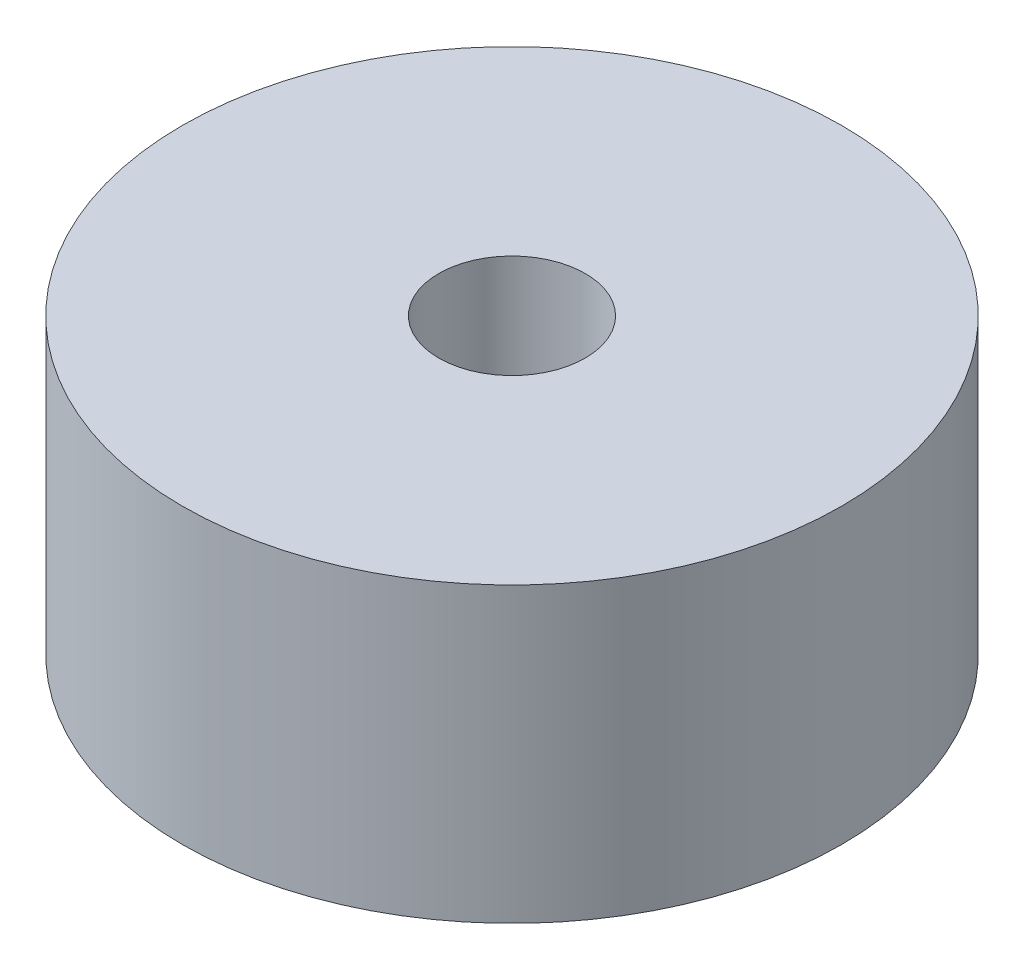
SolidWorks part; units mm, degrees
ref_plane "Front Plane" through (0, 0, 0) normal (0, 0, 1) x (1, 0, 0)
ref_plane "Top Plane" through (0, 0, 0) normal (0, 1, 0) x (1, 0, 0)
ref_plane "Right Plane" through (0, 0, 0) normal (1, 0, 0) x (0, 0, -1)
sketch "Sketch1" plane through (0, 0, 0) normal (0, 1, 0) x (1, 0, 0)
  circle A0 centre (0, 0) radius 4
  circle A1 centre (0, 0) radius 18
  dimension "D1" = 8
  dimension "D2" = 36
extrude "Boss-Extrude1" add sketch "Sketch1" along normal blind 16
